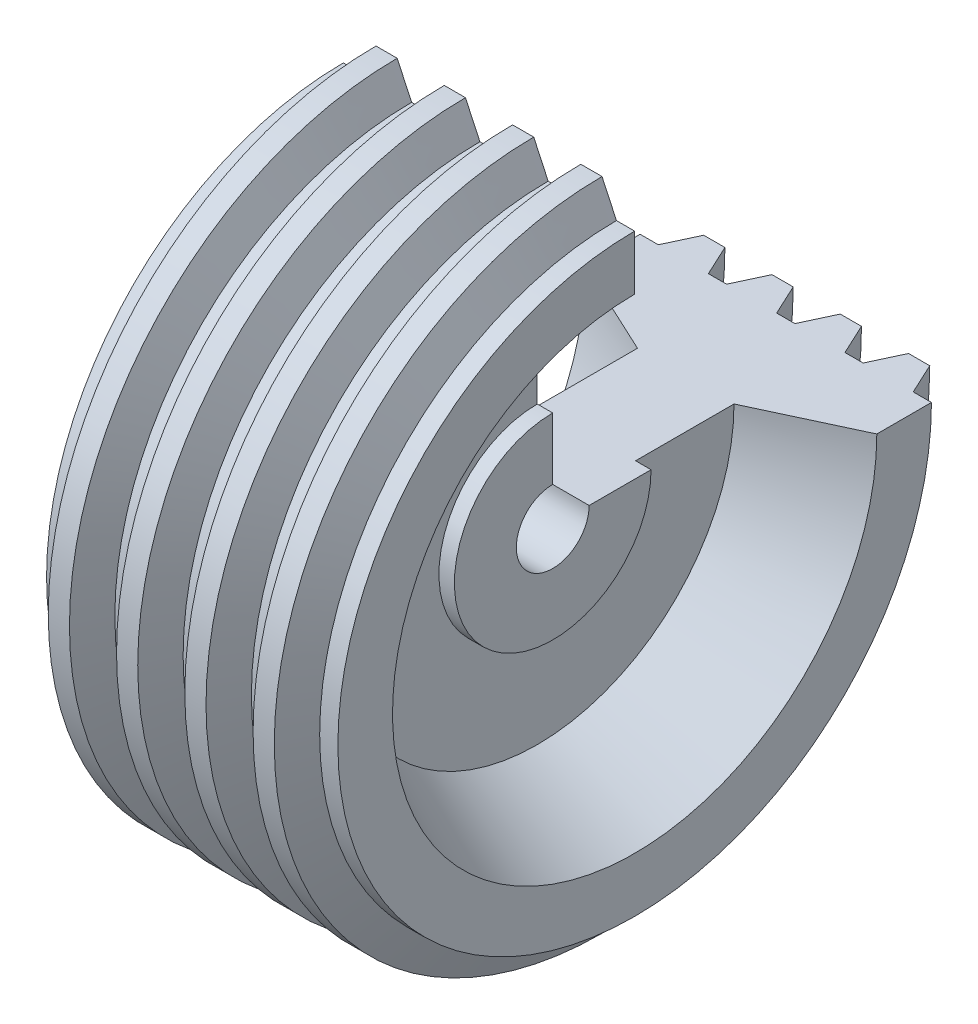
SolidWorks part; units mm, degrees
ref_plane "Front Plane" through (0, 0, 0) normal (0, 0, 1) x (1, 0, 0)
ref_plane "Top Plane" through (0, 0, 0) normal (0, 1, 0) x (1, 0, 0)
ref_plane "Right Plane" through (0, 0, 0) normal (1, 0, 0) x (0, 0, -1)
sketch "Sketch2" plane through (0, 0, 0) normal (0, 0, 1) x (1, 0, 0)
  line L0 (0, 0) -> (57564.0775, 0) construction
  line L1 (0, 0) -> (0, 57564.0775) construction
  line L2 (35, 20) -> (-35, 20)
  line L3 (-35, 20) -> (-35, 54)
  line L4 (-35, 54) -> (-26.5, 54)
  line L5 (-26.5, 54) -> (-26.5, 108.0525)
  line L6 (-26.5, 108.0525) -> (-80, 133)
  line L7 (-80, 133) -> (-80, 163)
  line L8 (-80, 163) -> (-70, 163)
  line L9 (-70, 163) -> (-62.0728, 180)
  line L10 (-62.0728, 180) -> (-50.4272, 180)
  line L11 (-50.4272, 180) -> (-42.5, 163)
  line L12 (-42.5, 163) -> (-32.5, 163)
  line L13 (-32.5, 163) -> (-24.5728, 180)
  line L14 (-24.5728, 180) -> (-12.9272, 180)
  line L15 (-12.9272, 180) -> (-5, 163)
  line L16 (-5, 163) -> (5, 163)
  line L17 (12.9272, 180) -> (5, 163)
  line L18 (24.5728, 180) -> (12.9272, 180)
  line L19 (32.5, 163) -> (24.5728, 180)
  line L20 (42.5, 163) -> (32.5, 163)
  line L21 (50.4272, 180) -> (42.5, 163)
  line L22 (62.0728, 180) -> (50.4272, 180)
  line L23 (70, 163) -> (62.0728, 180)
  line L24 (80, 163) -> (70, 163)
  line L25 (80, 133) -> (80, 163)
  line L26 (26.5, 108.0525) -> (80, 133)
  line L27 (26.5, 54) -> (26.5, 108.0525)
  line L28 (35, 54) -> (26.5, 54)
  line L29 (35, 20) -> (35, 54)
  point P5 (0, 0)
  point P22 (0, 163)
  point P35 (0, 20)
  point P36 (61.856, 129.7477)
  dimension "D1" = 70
  dimension "D2" = 40
  dimension "D3" = 53
  dimension "D4" = 108
  dimension "D5" = 360
  dimension "D6" = 17
  dimension "D7" = 160
  dimension "D8" = 65
  dimension "D9" = 10
  dimension "D10" = 30
revolve "Revolve1" add sketch "Sketch2" angle 270 about L0
